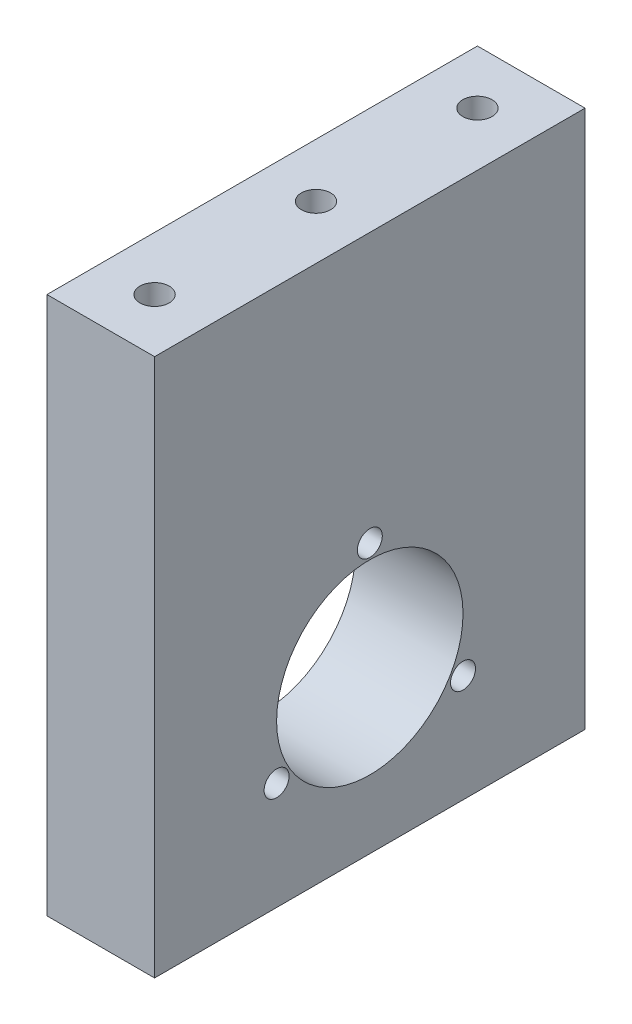
SolidWorks part; units mm, degrees
material "Nylon 6/10"
ref_plane "Front Plane" through (0, 0, 0) normal (0, 0, 1) x (1, 0, 0)
ref_plane "Top Plane" through (0, 0, 0) normal (0, 1, 0) x (1, 0, 0)
ref_plane "Right Plane" through (0, 0, 0) normal (1, 0, 0) x (0, 0, -1)
sketch "Sketch1" plane through (0, 0, 0) normal (1, 0, 0) x (0, 0, -1)
  line L1 (-25.4, -31.75) -> (25.4, -31.75)
  line L2 (-25.4, -31.75) -> (-25.4, 31.75)
  line L3 (-25.4, 31.75) -> (25.4, 31.75)
  line L4 (25.4, -31.75) -> (25.4, 31.75)
  line L5 (-25.4, -31.75) -> (25.4, 31.75) construction
  line L6 (-25.4, 31.75) -> (25.4, -31.75) construction
  point P0 (0, 0)
  dimension "D1" = 50.8
  dimension "D2" = 63.5
extrude "Boss-Extrude1" add sketch "Sketch1" along normal blind 12.7
hole_wizard "Ø22.0 (22) Diameter Hole1" positions "Sketch3" profile "Sketch2" hole size "Ø22.0" standard "ANSI Metric" end condition through all
sketch "Sketch3" plane through (12.7, 0, 0) normal (1, 0, 0) x (0, 0, -1)
  line L1 (25.4, 31.75) -> (-25.4, 31.75) construction
  line L2 (0, -31.75) -> (0, 31.75) construction
  line L3 (-25.4, -31.75) -> (25.4, -31.75) construction
  point P0 (0, -12.7)
  dimension "D1" = 44.45
sketch "Sketch2" plane through (12.7, -12.7, 0) normal (0, 1, 0) x (0, 0, -1)
  line L0 (0, 0) -> (0, 12.7)
  line L1 (0, 12.7) -> (11, 12.7)
  line L2 (11, 12.7) -> (11, 0)
  line L5 (11, 0) -> (0, 0)
  line L11 (0, -6.35) -> (0, 107.95) construction
  dimension "Thru Hole Dia." = 22
  dimension "Thru Hole Depth" = 12.7
hole_wizard "#8-32 Tapped Hole1" positions "Sketch12" profile "Sketch11" tap size "#8-32" standard "ANSI Inch"
sketch "Sketch12" plane through (0, 31.75, 0) normal (0, 1, 0) x (1, 0, 0)
  line L0 (6.35, 25.4) -> (6.35, -25.4) construction
  line L1 (12.7, 25.4) -> (0, 25.4) construction
  line L2 (12.7, -25.4) -> (0, -25.4) construction
  line L3 (12.7, 0) -> (0, 0) construction
  line L4 (12.7, 25.4) -> (12.7, -25.4) construction
  line L5 (0, 25.4) -> (0, -25.4) construction
  point P0 (6.35, 19.05)
  point P2 (6.35, -19.05)
  point P13 (6.35, 0)
  dimension "D1" = 6.35
  dimension "D2" = 6.35
sketch "Sketch11" plane through (6.35, 31.75, -19.05) normal (1, 0, 0) x (0, 0, 1)
  line L0 (0, 0) -> (0, 11.7058)
  line L1 (0, 11.7058) -> (1.7272, 10.668)
  line L2 (1.7272, 10.668) -> (1.7272, 0)
  line L5 (1.7272, 0) -> (0, 0)
  line L10 (0, 11.7058) -> (-1.7272, 10.668) construction
  line L11 (0, -6.35) -> (0, 107.95) construction
  dimension "Tap Drill Dia." = 3.4544
  dimension "Tap Drill Depth" = 10.668
  dimension "Drill Angle" = 118
hole_wizard "#4 Clearance Hole1" positions "Sketch14" profile "Sketch13" hole size "#4" standard "ANSI Inch" end condition through all
sketch "Sketch14" plane through (0, 0, 0) normal (-1, 0, 0) x (0, 0, 1)
  line L0 (0, 31.75) -> (0, -31.75) construction
  line L1 (-25.4, 31.75) -> (25.4, 31.75) construction
  line L2 (25.4, -31.75) -> (-25.4, -31.75) construction
  circle A0 centre (0, -12.7) radius 11 construction
  point P0 (0, 0)
  dimension "D1" = 12.7
sketch "Sketch13" plane through (0, 0, 0) normal (0, 1, 0) x (0, 0, 1)
  line L0 (0, 0) -> (0, 12.7)
  line L1 (0, 12.7) -> (1.4732, 12.7)
  line L2 (1.4732, 12.7) -> (1.4732, 0)
  line L5 (1.4732, 0) -> (0, 0)
  line L11 (0, -6.35) -> (0, 107.95) construction
  dimension "Thru Hole Dia." = 2.9464
  dimension "Thru Hole Depth" = 12.7
pattern_circular "CirPattern1" count 3 over 360 about axis through (0, -12.7, 0) along (1, 0, 0) of "#4 Clearance Hole1"
